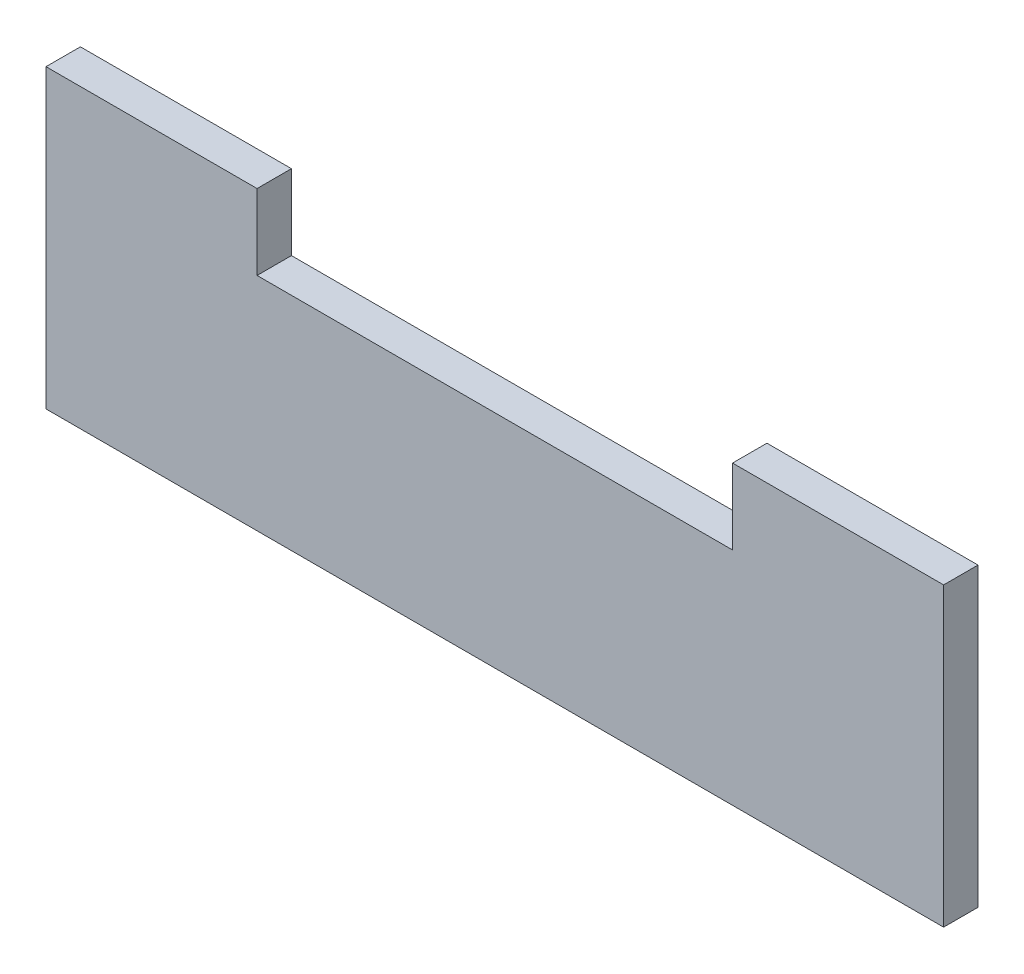
SolidWorks part; units mm, degrees
ref_plane "Front Plane" through (0, 0, 0) normal (0, 0, 1) x (1, 0, 0)
ref_plane "Top Plane" through (0, 0, 0) normal (0, 1, 0) x (1, 0, 0)
ref_plane "Right Plane" through (0, 0, 0) normal (1, 0, 0) x (0, 0, -1)
sketch "Sketch1" plane through (0, 0, 0) normal (0, 0, 1) x (1, 0, 0)
  line L0 (-37.85, 0) -> (37.85, 0)
  line L1 (37.85, 0) -> (37.85, 25)
  line L2 (37.85, 25) -> (20.05, 25)
  line L3 (20.05, 25) -> (20.05, 18.65)
  line L4 (20.05, 18.65) -> (-20.05, 18.65)
  line L5 (-20.05, 18.65) -> (-20.05, 25)
  line L6 (-20.05, 25) -> (-37.85, 25)
  line L7 (-37.85, 25) -> (-37.85, 0)
  point P8 (0, 0)
  dimension "D1" = 17.8
  dimension "D2" = 6.35
  dimension "D3" = 25
  dimension "D4" = 40.1
extrude "Boss-Extrude1" add sketch "Sketch1" along normal blind 2.9
